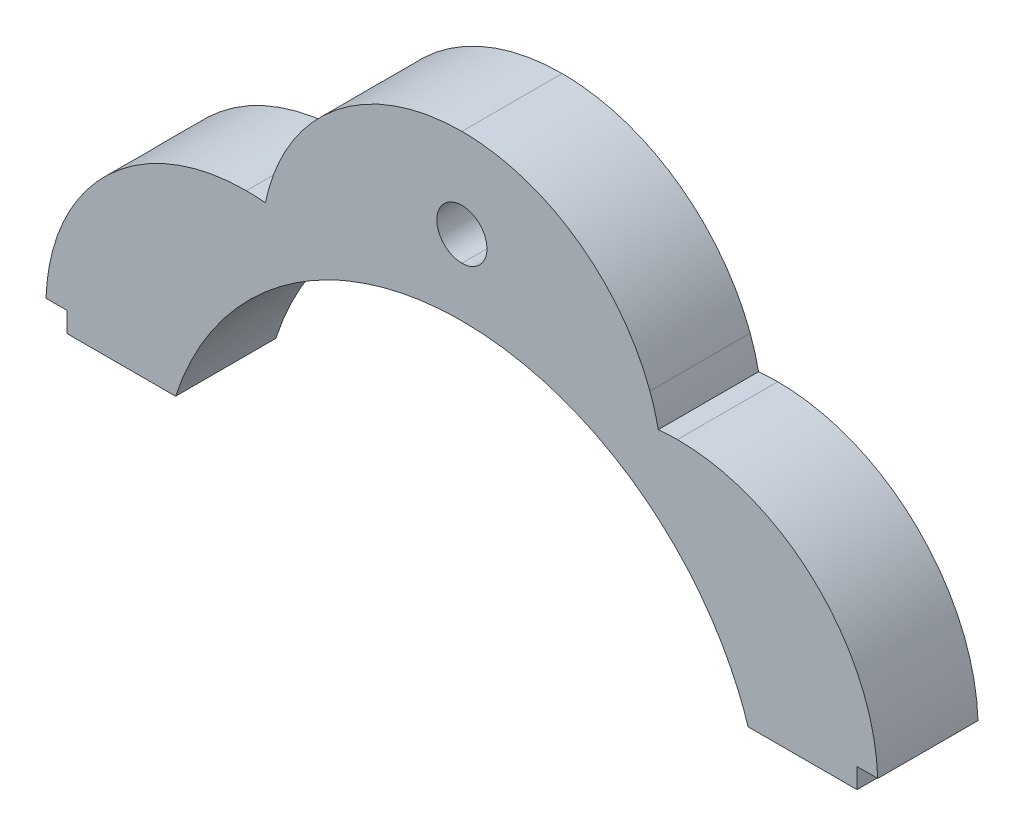
SolidWorks part; units mm, degrees
ref_plane "前视基准面" through (0, 0, 0) normal (0, 0, 1) x (1, 0, 0)
ref_plane "上视基准面" through (0, 0, 0) normal (0, 1, 0) x (1, 0, 0)
ref_plane "右视基准面" through (0, 0, 0) normal (1, 0, 0) x (0, 0, -1)
other "Configuration Table"
sketch "草图1" plane through (0, 0, 0) normal (0, 0, 1) x (1, 0, 0)
  line L0 (-93.656, -14.8911) -> (-91.5852, -14.8911)
  line L1 (-91.5852, -14.8911) -> (-91.5852, -16.8914)
  line L2 (-91.5852, -16.8914) -> (-80.7267, -16.8914)
  line L3 (-23.612, -16.8914) -> (-12.7535, -16.8914)
  line L4 (-12.7535, -16.8914) -> (-12.7535, -14.8911)
  line L5 (-12.7535, -14.8911) -> (-10.6827, -14.8911)
  spline S0 degree 3 poles (-30.6675, 4.3952) (-31.3096, 4.3952) (-31.9481, 4.3635) (-32.5761, 4.3035) knots 0 0 0 0 1 1 1 1
  spline S1 degree 3 poles (-32.5761, 4.3035) (-32.7807, 5.3019) (-33.0629, 6.2755) (-33.4086, 7.2174) knots 1 1 1 1 2 2 2 2
  spline S2 degree 3 poles (-33.4086, 7.2174) (-36.2308, 14.8375) (-43.5651, 20.2702) (-52.1693, 20.2702) knots 2 2 2 2 3 3 3 3
  spline S3 degree 3 poles (-52.1693, 20.2702) (-60.7736, 20.2702) (-68.1078, 14.8375) (-70.93, 7.2174) knots 3 3 3 3 4 4 4 4
  spline S4 degree 3 poles (-70.93, 7.2174) (-71.2758, 6.2755) (-71.558, 5.3019) (-71.7626, 4.3035) knots 4 4 4 4 5 5 5 5
  spline S5 degree 3 poles (-71.7626, 4.3035) (-72.3906, 4.3635) (-73.0255, 4.3952) (-73.6676, 4.3952) knots 5 5 5 5 6 6 6 6
  spline S6 degree 3 poles (-73.6676, 4.3952) (-84.4767, 4.3952) (-93.282, -4.1737) (-93.656, -14.8911) knots 6 6 6 6 7 7 7 7
  spline S7 degree 3 poles (-80.7267, -16.8914) (-79.0298, -11.6209) (-75.9113, -6.9854) (-71.8226, -3.4365) knots 10 10 10 10 11 11 11 11
  spline S8 degree 3 poles (-71.8226, -3.4365) (-69.3813, -1.3198) (-66.5979, 0.4124) (-63.5605, 1.6577) knots 11 11 11 11 12 12 12 12
  spline S9 degree 3 poles (-63.5605, 1.6577) (-60.0469, 3.1005) (-56.2016, 3.8978) (-52.1693, 3.8978) knots 12 12 12 12 13 13 13 13
  spline S10 degree 3 poles (-52.1693, 3.8978) (-48.1371, 3.8978) (-44.2883, 3.1005) (-40.7746, 1.6542) knots 13 13 13 13 14 14 14 14
  spline S11 degree 3 poles (-40.7746, 1.6542) (-37.7407, 0.4088) (-34.9538, -1.3198) (-32.5161, -3.4365) knots 14 14 14 14 15 15 15 15
  spline S12 degree 3 poles (-32.5161, -3.4365) (-28.4274, -6.9854) (-25.3088, -11.6209) (-23.612, -16.8914) knots 15 15 15 15 16 16 16 16
  spline S13 degree 3 poles (-10.6827, -14.8911) (-11.0566, -4.1737) (-19.8619, 4.3952) (-30.6675, 4.3952) knots 19 19 19 19 20 20 20 20
  spline S14 degree 3 poles (-52.1693, 8.8826) (-53.5487, 8.8826) (-54.6705, 10.0044) (-54.6705, 11.3837) (-54.6705, 12.7631) (-53.5487, 13.885) (-52.1693, 13.885) knots 2 2 2 2 3 3 3 4 4 4 4
  spline S15 degree 3 poles (-52.1693, 13.885) (-50.79, 13.885) (-49.6681, 12.7631) (-49.6681, 11.3837) (-49.6681, 10.0044) (-50.79, 8.8826) (-52.1693, 8.8826) knots 0 0 0 0 1 1 1 2 2 2 2
extrude "凸台-拉伸1" add sketch "草图1" along normal blind 10
